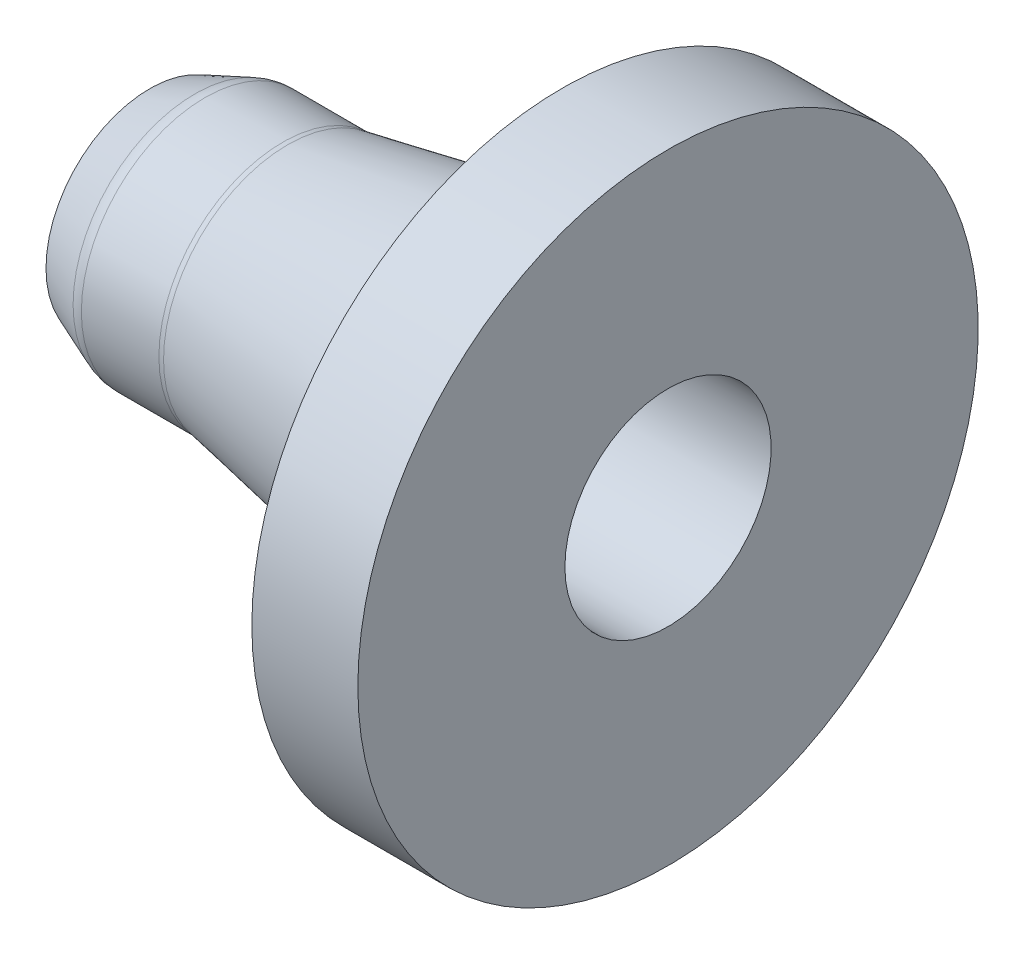
SolidWorks part; units mm, degrees
ref_plane "Front Plane" through (0, 0, 0) normal (0, 0, 1) x (1, 0, 0)
ref_plane "Top Plane" through (0, 0, 0) normal (0, 1, 0) x (1, 0, 0)
ref_plane "Right Plane" through (0, 0, 0) normal (1, 0, 0) x (0, 0, -1)
sketch "Sketch1" plane through (0, 0, 0) normal (0, 0, 1) x (1, 0, 0)
  line L0 (0.024, 0.75) -> (0.024, 0.7542)
  line L1 (0.024, 0.7542) -> (0.3883, 0.9)
  line L2 (0.3883, 0.9) -> (1.0097, 0.9)
  line L3 (1.0097, 0.9) -> (2.2733, 1.1403)
  line L4 (2.2733, 1.1403) -> (2.2733, 0.9652)
  line L5 (2.2733, 0.9652) -> (3.0229, 0.9652)
  line L7 (3.0229, 0.9652) -> (3.0229, 2.256)
  line L8 (0, 0) -> (9.01, 0) construction
  line L9 (3.0229, 2.256) -> (3.794, 2.256)
  line L10 (3.794, 2.256) -> (3.794, 0.9)
  line L14 (3.794, 0.9) -> (3.794, 0.75)
  line L15 (3.794, 0.75) -> (0.024, 0.75)
  point P2 (7.0303, 1.2911)
  point P3 (2.6007, 1.4686)
  point P9 (0, 0.5)
  point P12 (0, 0.5)
  point P13 (0, 0.5)
  point P14 (4.638, 1.0673)
  point P16 (4.638, 1.1136)
  point P18 (2.3239, 1.2308)
  point P19 (0.993, 0.9)
  point P20 (2.2967, 1.2716)
  point P21 (0, 0.7446)
  point P25 (0.3883, 0.9)
  point P26 (1.0097, 0.9)
  point P27 (0, 0)
  point P28 (2.2733, 1.1403)
  dimension "D1" = 3.77
  dimension "D2" = 0.9
  dimension "D3" = 0.75
  dimension "D4" = 0.771
  dimension "D5" = 2.256
revolve "Revolve1" add sketch "Sketch1" angle 360 about L8
fillet "Fillet1" radius 0.2 2 edges at (0.3883, 0, 0.9) (1.0097, 0, 0.9)
